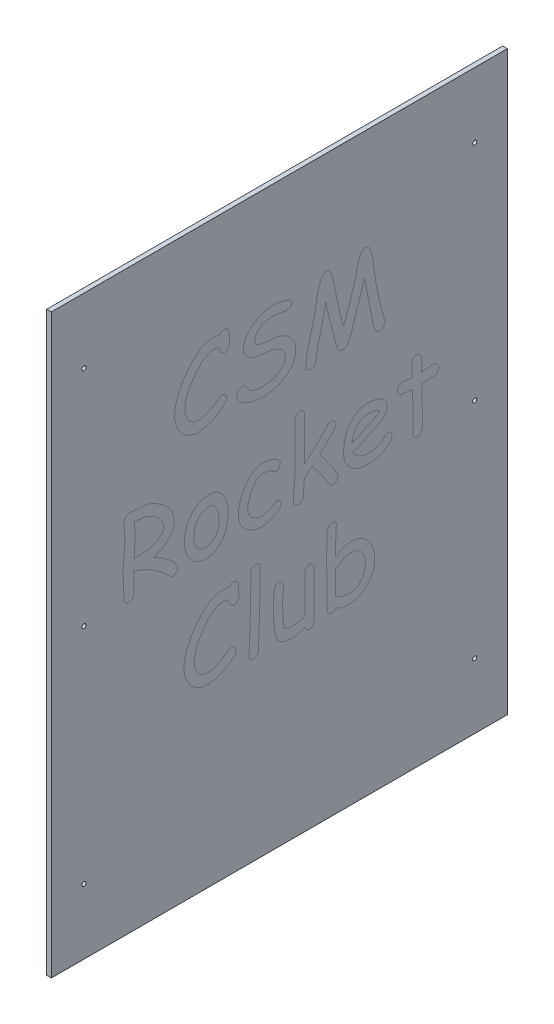
SolidWorks part; units mm, degrees
material "Beech"
ref_plane "Front Plane" through (0, 0, 0) normal (0, 0, 1) x (1, 0, 0)
ref_plane "Top Plane" through (0, 0, 0) normal (0, 1, 0) x (1, 0, 0)
ref_plane "Right Plane" through (0, 0, 0) normal (1, 0, 0) x (0, 0, -1)
sketch "Sketch1" plane through (0, 0, 0) normal (1, 0, 0) x (0, 0, -1)
  line L1 (-311.15, -393.7) -> (311.15, -393.7)
  line L2 (-311.15, -393.7) -> (-311.15, 393.7)
  line L3 (-311.15, 393.7) -> (311.15, 393.7)
  line L4 (311.15, -393.7) -> (311.15, 393.7)
  line L5 (-311.15, -393.7) -> (311.15, 393.7) construction
  line L6 (-311.15, 393.7) -> (311.15, -393.7) construction
  point P0 (0, 0)
  dimension "D1" = 787.4
  dimension "D2" = 622.3
extrude "Boss-Extrude1" add sketch "Sketch1" along normal blind 6.35
sketch "Sketch2" plane through (6.35, 0, 0) normal (1, 0, 0) x (0, 0, -1)
  line L0 (-311.15, 152.4) -> (311.15, 152.4) construction
  line L1 (-311.15, 0) -> (311.15, 0) construction
  line L2 (-311.15, -152.4) -> (311.15, -152.4) construction
  line L3 (-311.15, 393.7) -> (-311.15, -393.7) construction
  line L4 (311.15, -393.7) -> (311.15, 393.7) construction
  text T0 "CSM" font "Comic Sans MS" height 101.6
  text T1 "Rocket" font "Comic Sans MS" height 101.6
  text T2 "Club" font "Comic Sans MS" height 101.6
  point P8 (-311.15, 152.4)
  point P11 (311.15, 152.4)
  point P14 (-311.15, 0)
  point P15 (311.15, 0)
  point P16 (311.15, -152.4)
  point P17 (-311.15, -152.4)
  dimension "D1" = 152.4
  dimension "D2" = 152.4
split line "Split Line1"
hole_wizard "#10 Clearance Hole1" positions "Sketch4" profile "Sketch5" hole size "#10" standard "ANSI Inch" end condition through all
sketch "Sketch4" plane through (6.35, 0, 0) normal (1, 0, 0) x (0, 0, -1)
  line L0 (-266.7, 304.8) -> (-266.7, 0) construction
  line L1 (-266.7, 0) -> (-266.7, -304.8) construction
  line L3 (266.7, -304.8) -> (266.7, 0) construction
  line L4 (266.7, 0) -> (266.7, 304.8) construction
  line L6 (-311.15, 393.7) -> (-311.15, -393.7) construction
  line L7 (311.15, -393.7) -> (311.15, 393.7) construction
  point P0 (-266.7, -304.8)
  point P2 (-266.7, 0)
  point P4 (-266.7, 304.8)
  point P6 (266.7, 304.8)
  point P8 (266.7, 0)
  point P10 (266.7, -304.8)
  dimension "D1" = 44.45
  dimension "D2" = 44.45
  dimension "D3" = 304.8
sketch "Sketch5" plane through (6.35, -304.8, 266.7) normal (0, 1, 0) x (0, 0, -1)
  line L0 (0, 0) -> (0, 6.35)
  line L1 (0, 6.35) -> (2.8067, 6.35)
  line L2 (2.8067, 6.35) -> (2.8067, 0)
  line L5 (2.8067, 0) -> (0, 0)
  line L11 (0, -6.35) -> (0, 107.95) construction
  dimension "Thru Hole Dia." = 5.6134
  dimension "Thru Hole Depth" = 6.35
